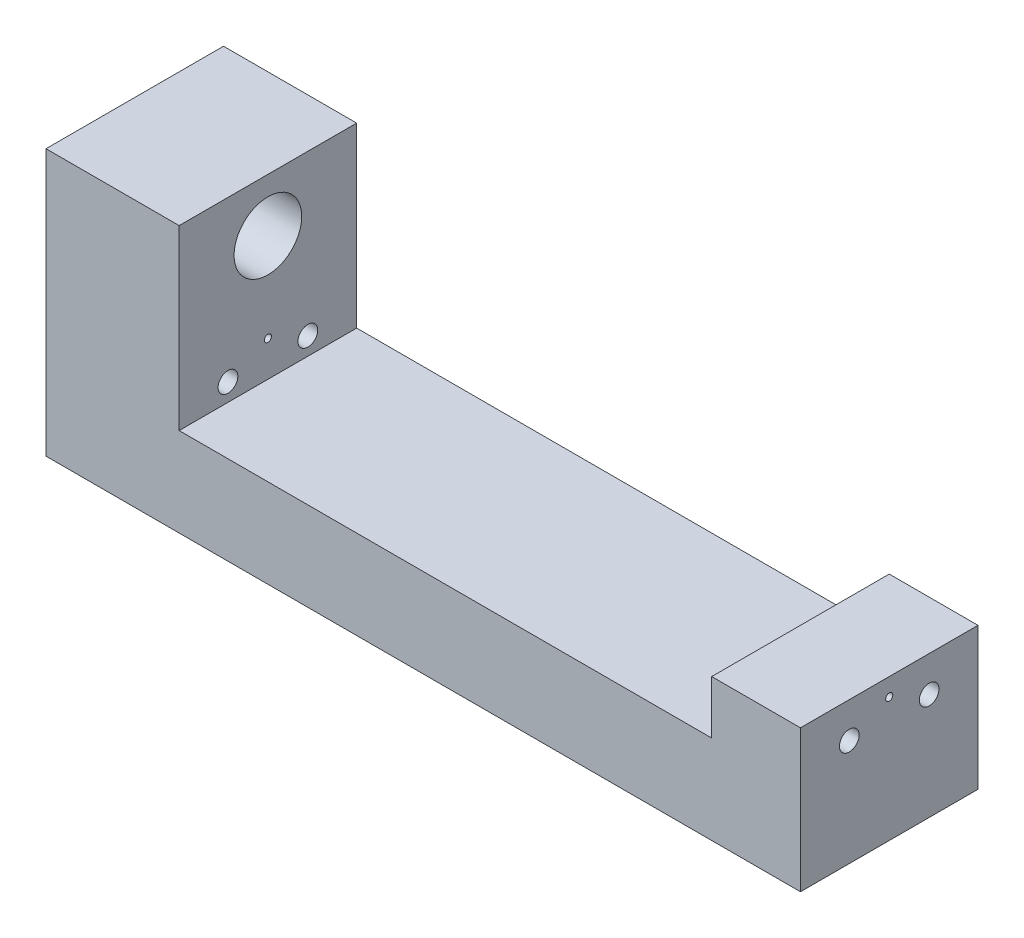
SolidWorks part; units mm, degrees
material "Ceramic Porcelain"
ref_plane "Front Plane" through (0, 0, 0) normal (0, 0, 1) x (1, 0, 0)
ref_plane "Top Plane" through (0, 0, 0) normal (0, 1, 0) x (1, 0, 0)
ref_plane "Right Plane" through (0, 0, 0) normal (1, 0, 0) x (0, 0, -1)
sketch "Sketch1" plane through (0, 0, 0) normal (0, 1, 0) x (1, 0, 0)
  line L1 (0, 0) -> (850, 0)
  line L2 (0, 0) -> (0, 200)
  line L3 (0, 200) -> (850, 200)
  line L4 (850, 0) -> (850, 200)
  dimension "D1" = 850
  dimension "D2" = 200
extrude "Boss-Extrude1" add sketch "Sketch1" along normal blind 100
sketch "Sketch2" plane through (0, 100, 0) normal (0, 1, 0) x (1, 0, 0)
  line L0 (850, 200) -> (0, 200) construction
  line L1 (0, 0) -> (150, 0)
  line L2 (0, 0) -> (0, 200)
  line L3 (0, 200) -> (150, 200)
  line L4 (150, 0) -> (150, 200)
  dimension "D1" = 150
extrude "Boss-Extrude2" add sketch "Sketch2" along normal blind 200
sketch "Sketch4" plane through (0, 100, 0) normal (0, 1, 0) x (1, 0, 0)
  line L0 (850, 200) -> (150, 200) construction
  line L1 (850, 0) -> (750, 0)
  line L2 (850, 0) -> (850, 200)
  line L3 (850, 200) -> (750, 200)
  line L4 (750, 0) -> (750, 200)
  dimension "D1" = 100
extrude "Boss-Extrude3" add sketch "Sketch4" along normal blind 60
sketch "Sketch3" plane through (0, 0, 0) normal (-1, 0, 0) x (0, 0, 1)
  line L0 (-200, 300) -> (0, 300) construction
  line L1 (-100, 0) -> (-100, 300) construction
  line L2 (-200, 0) -> (0, 0) construction
  circle A0 centre (-100, 240) radius 38.1
  circle A1 centre (-145, 120) radius 11.11
  circle A2 centre (-55, 120) radius 11.11
  circle A3 centre (-100, 140) radius 4
  point P4 (-100, 300)
  dimension "D1" = 76.2
  dimension "D3" = 90
  dimension "D4" = 22.22
  dimension "D5" = 20
  dimension "D6" = 8
  dimension "D7" = 20
  dimension "D2" = 60
extrude "Cut-Extrude1" cut sketch "Sketch3" against normal through all both and the other way through all
